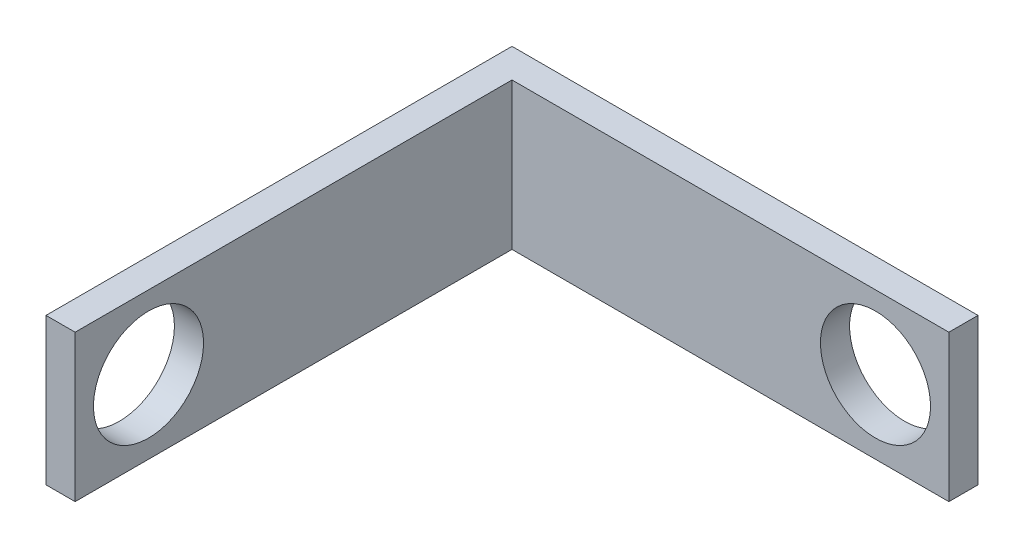
SolidWorks part; units mm, degrees
ref_plane "Front Plane" through (0, 0, 0) normal (0, 0, 1) x (1, 0, 0)
ref_plane "Top Plane" through (0, 0, 0) normal (0, 1, 0) x (1, 0, 0)
ref_plane "Right Plane" through (0, 0, 0) normal (1, 0, 0) x (0, 0, -1)
sketch "Sketch1" plane through (0, 0, 0) normal (0, 1, 0) x (1, 0, 0)
  line L0 (-20.6062, 0) -> (0, 0) construction
  line L1 (-4, 19.8125) -> (4, 19.8125)
  line L2 (-4, 19.8125) -> (-4, 21.4) construction
  line L3 (-4, 21.4) -> (4, 21.4)
  line L4 (4, 19.8125) -> (4, 21.4)
  line L5 (-4, 19.8125) -> (4, 21.4) construction
  line L6 (-4, 21.4) -> (4, 19.8125) construction
  line L7 (-21.4, 4) -> (-19.8125, 4) construction
  line L8 (-21.4, 4) -> (-21.4, -4)
  line L9 (-21.4, -4) -> (-19.8125, -4)
  line L10 (-19.8125, 4) -> (-19.8125, -4)
  line L11 (-21.4, 4) -> (-19.8125, -4) construction
  line L12 (-21.4, -4) -> (-19.8125, 4) construction
  line L13 (0, 0) -> (0, 20.6062) construction
  line L14 (-19.8125, 4) -> (-19.8125, 19.8125)
  line L15 (-19.8125, 19.8125) -> (-4, 19.8125)
  line L16 (-4, 21.4) -> (-21.4, 21.4)
  line L17 (-21.4, 21.4) -> (-21.4, 4)
  arc A0 (-19.8125, 4) -> (-4, 19.8125) centre (-4, 4) cw construction
  arc A1 (-21.4, 4) -> (-4, 21.4) centre (-4, 4) cw construction
  point P0 (0, 20.6062)
  point P5 (-20.6062, 0)
  dimension "D3" = 25.4
  dimension "D1" = 1.5875
  dimension "D2" = 8
extrude "Boss-Extrude1" add sketch "Sketch1" along normal mid plane 8 contours L10 L7 L8 L9 | L1 L4 L3 L2
sketch "Sketch2" plane through (-19.8125, 0, 0) normal (1, 0, 0) x (0, 0, -1)
  circle A0 centre (0, 0) radius 3
  dimension "D1" = 6
extrude "Cut-Extrude1" cut sketch "Sketch2" against normal through all
sketch "Sketch3" plane through (0, 0, -19.8125) normal (0, 0, 1) x (1, 0, 0)
  circle A0 centre (0, 0) radius 3
  dimension "D1" = 6
extrude "Cut-Extrude2" cut sketch "Sketch3" against normal through all
